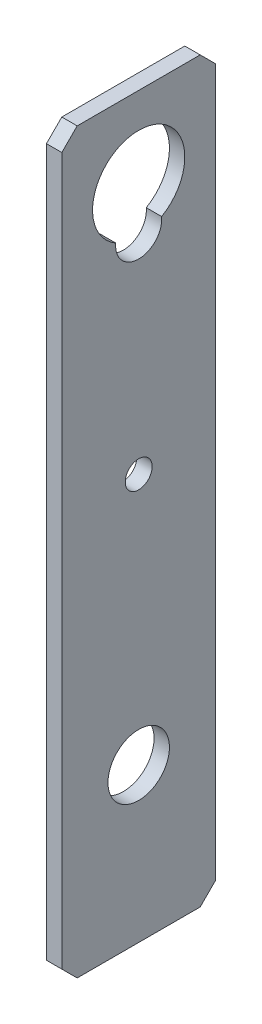
SolidWorks part; units mm, degrees
ref_plane "Front Plane" through (0, 0, 0) normal (0, 0, 1) x (1, 0, 0)
ref_plane "Top Plane" through (0, 0, 0) normal (0, 1, 0) x (1, 0, 0)
ref_plane "Right Plane" through (0, 0, 0) normal (1, 0, 0) x (0, 0, -1)
sketch "Sketch1" plane through (0, 0, 0) normal (1, 0, 0) x (0, 0, -1)
  line L1 (0, 0) -> (20, 0)
  line L2 (0, 0) -> (0, 96)
  line L3 (0, 96) -> (20, 96)
  line L4 (20, 0) -> (20, 96)
  dimension "D1" = 20
  dimension "D2" = 96
extrude "Boss-Extrude1" add sketch "Sketch1" along normal blind 2
sketch "Sketch2" plane through (2, 0, 0) normal (1, 0, 0) x (0, 0, -1)
  line L0 (10, 96) -> (10, 0) construction
  line L1 (20, 96) -> (0, 96) construction
  line L2 (0, 0) -> (20, 0) construction
  arc A0 (12.9854, 80.2955) -> (7.0146, 80.2955) centre (10, 85.5) ccw
  circle A1 centre (10, 52.75) radius 1.75
  circle A2 centre (10, 20) radius 4
  arc A3 (7.0146, 80.2955) -> (12.9854, 80.2955) centre (10, 80) ccw
  dimension "D1" = 8
  dimension "D2" = 3.5
  dimension "D3" = 12
  dimension "D5" = 32.75
  dimension "D7" = 6
  dimension "D8" = 0.5
  dimension "D4" = 20
  dimension "D6" = 10.5
extrude "Cut-Extrude1" cut sketch "Sketch2" against normal through all
chamfer "Chamfer1" distance 2 angle 45 4 edges at (1, 0, -20) (1, 0, 0) (1, 96, -20) (1, 96, 0)
